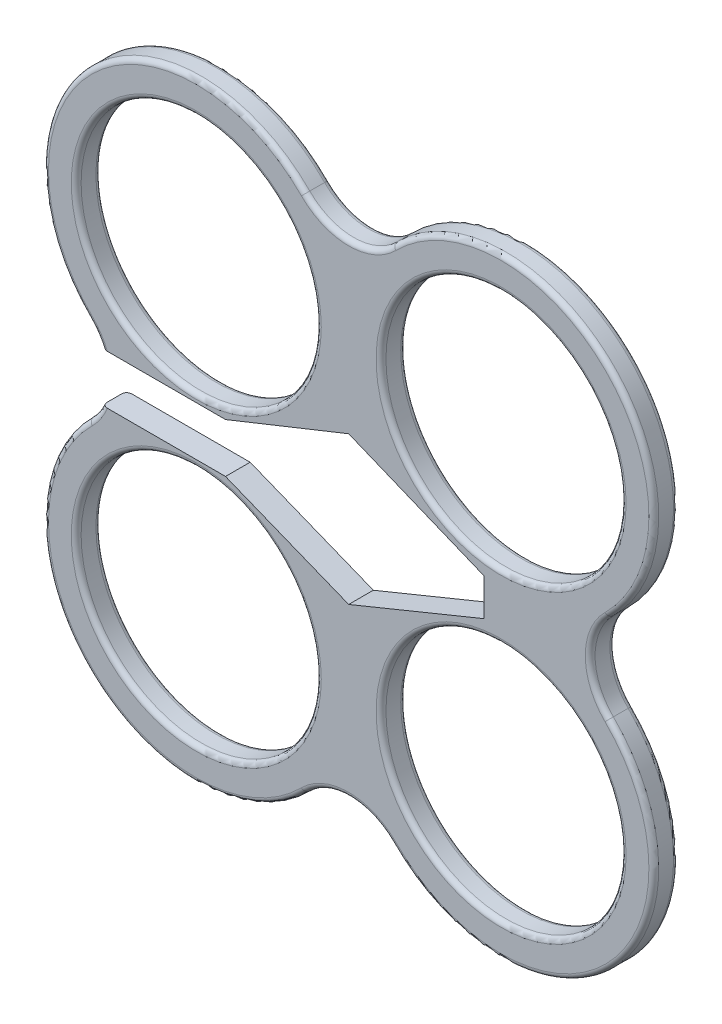
SolidWorks part; units mm, degrees
ref_plane "Plan de face" through (0, 0, 0) normal (0, 0, 1) x (1, 0, 0)
ref_plane "Plan de dessus" through (0, 0, 0) normal (0, 1, 0) x (1, 0, 0)
ref_plane "Plan de droite" through (0, 0, 0) normal (1, 0, 0) x (0, 0, -1)
sketch "Esquisse1" plane through (0, 0, 0) normal (0, 0, 1) x (1, 0, 0)
  line L0 (-200.2433, 20) -> (-100, 20)
  line L1 (-100, 20) -> (0, 60)
  line L2 (0, 60) -> (110, 15)
  line L3 (110, 15) -> (110, 0)
  line L4 (-269.8058, 0) -> (326.1689, 0) construction
  line L5 (-296.7371, 0) -> (304.3188, 0) construction
  line L6 (110, -15) -> (110, 0)
  line L7 (0, -60) -> (110, -15)
  line L8 (-100, -20) -> (0, -60)
  line L9 (-200.2433, -20) -> (-100, -20)
  line L10 (-209.5, -12) -> (-130, -12) construction
  circle A0 centre (123.7437, 123.7437) radius 97.5
  circle A2 centre (-123.7437, 123.7437) radius 97.5
  circle A3 centre (-123.7437, -123.7437) radius 97.5
  circle A5 centre (123.7437, -123.7437) radius 97.5
  arc A6 (210.9181, 35.5585) -> (35.5585, 210.9181) centre (123.7437, 123.7437) ccw
  arc A7 (-35.5585, 210.9181) -> (-210.9181, 35.5585) centre (-123.7437, 123.7437) ccw
  arc A8 (-210.9181, -35.5585) -> (-35.5585, -210.9181) centre (-123.7437, -123.7437) ccw
  arc A9 (35.5585, -210.9181) -> (210.9181, -35.5585) centre (123.7437, -123.7437) ccw
  arc A10 (210.9181, 35.5585) -> (210.9181, -35.5585) centre (246.0691, 0) ccw
  arc A11 (-210.9181, -35.5585) -> (-200.2433, -20) centre (-246.0691, 0) ccw
  arc A12 (35.5585, -210.9181) -> (-35.5585, -210.9181) centre (0, -246.0691) ccw
  arc A13 (-35.5585, 210.9181) -> (35.5585, 210.9181) centre (0, 246.0691) ccw
  arc A14 (-200.2433, 20) -> (-210.9181, 35.5585) centre (-246.0691, 0) ccw
  dimension "D1" = 195
  dimension "D2" = 124
  dimension "D3" = 50
  dimension "D4" = 8
  dimension "D5" = 120
  dimension "D6" = 30
  dimension "D7" = 110
  dimension "D8" = 100
extrude "Boss.-Extru.1" add sketch "Esquisse1" along normal mid plane 20
fillet "Congé1" radius 4 26 edges at (221.2437, -123.7437, -10) (-26.2437, -123.7437, -10) (211.4249, 211.4249, -10) (0, 196.0691, -10) (-211.4249, 211.4249, -10) (-204.8401, 28.2874, -10) (-204.8401, -28.2874, -10) (-211.4249, -211.4249, -10) (0, -196.0691, -10) (211.4249, -211.4249, -10) (196.0691, 0, -10) (221.2437, 123.7437, -10) (-26.2437, 123.7437, -10) (221.2437, -123.7437, 10) (-26.2437, -123.7437, 10) (211.4249, -211.4249, 10) (0, -196.0691, 10) (-211.4249, -211.4249, 10) (-204.8401, -28.2874, 10) (-204.8401, 28.2874, 10) (-211.4249, 211.4249, 10) (0, 196.0691, 10) (211.4249, 211.4249, 10) (196.0691, 0, 10) (221.2437, 123.7437, 10) (-26.2437, 123.7437, 10)
